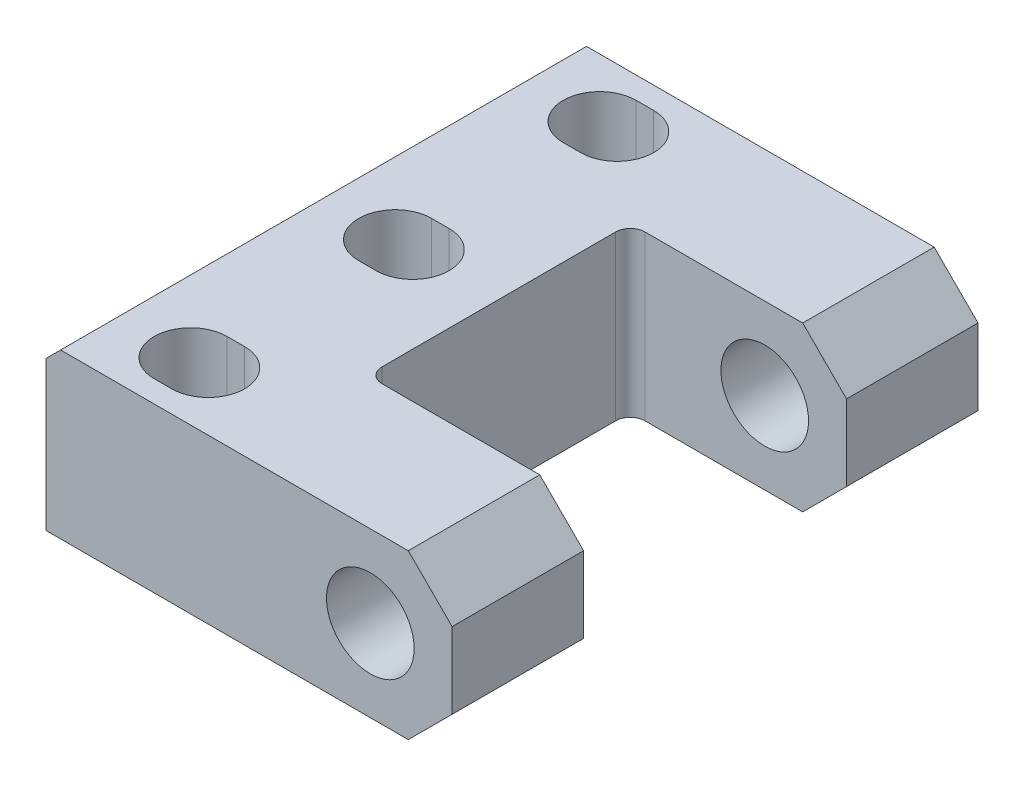
SolidWorks part; units mm, degrees
ref_plane "前视基准面" through (0, 0, 0) normal (0, 0, 1) x (1, 0, 0)
ref_plane "上视基准面" through (0, 0, 0) normal (0, 1, 0) x (1, 0, 0)
ref_plane "右视基准面" through (0, 0, 0) normal (1, 0, 0) x (0, 0, -1)
sketch "草图1" plane through (0, 0, 0) normal (0, 1, 0) x (1, 0, 0)
  line L0 (0, -90) -> (0, 90)
  line L1 (0, 90) -> (139, 90)
  line L2 (139, 90) -> (139, 45)
  line L3 (139, 45) -> (65, 45)
  line L4 (65, 45) -> (65, -45)
  line L5 (0, 0) -> (-68.1514, 0) construction
  line L6 (139, -45) -> (65, -45)
  line L7 (139, -90) -> (139, -45)
  line L8 (0, -90) -> (139, -90)
  point P9 (65, 0)
  dimension "D1" = 180
  dimension "D2" = 90
  dimension "D3" = 139
  dimension "D4" = 74
extrude "凸台-拉伸1" add sketch "草图1" against normal blind 56
sketch "草图2" plane through (0, 0, 0) normal (0, 1, 0) x (1, 0, 0)
  line L0 (0, 0) -> (-30.2002, 0) construction
  line L1 (0, 90) -> (0, -90) construction
  line L2 (29.5, 70) -> (35.5, 70) construction
  line L3 (29.5, 78.5) -> (35.5, 78.5)
  line L4 (29.5, 61.5) -> (35.5, 61.5)
  arc A0 (29.5, 78.5) -> (29.5, 61.5) centre (29.5, 70) ccw
  arc A1 (35.5, 61.5) -> (35.5, 78.5) centre (35.5, 70) ccw
  point P6 (32.5, 70)
  dimension "D1" = 17
  dimension "D2" = 6
  dimension "D3" = 32.5
  dimension "D4" = 70
extrude "切除-拉伸1" cut sketch "草图2" against normal up to next
sketch "草图3" plane through (0, 0, 0) normal (0, 1, 0) x (1, 0, 0)
  line L8 (139, 90) -> (0, 90)
  line L9 (0, 90) -> (0, -90)
  line L10 (0, -90) -> (139, -90)
  line L11 (139, -90) -> (139, -45)
  line L12 (139, -45) -> (65, -45)
  line L13 (65, -45) -> (65, 45)
  line L14 (65, 45) -> (139, 45)
  line L15 (139, 45) -> (139, 90)
  line L16 (139, 90) -> (0, 90)
  line L17 (0, 90) -> (0, -90)
  line L18 (0, -90) -> (139, -90)
  line L19 (139, -90) -> (139, -45)
  line L20 (139, -45) -> (65, -45)
  line L21 (65, -45) -> (65, 45)
  line L22 (65, 45) -> (139, 45)
  line L23 (139, 45) -> (139, 90)
  line L27 (29.5, 57.5) -> (35.5, 57.5)
  line L28 (35.5, 82.5) -> (29.5, 82.5)
  line L29 (29.5, 57.5) -> (35.5, 57.5)
  line L30 (35.5, 82.5) -> (29.5, 82.5)
  arc A2 (35.5, 61.5) -> (35.5, 78.5) centre (35.5, 70) ccw construction
  arc A15 (35.5, 57.5) -> (35.5, 82.5) centre (35.5, 70) ccw
  arc A16 (29.5, 82.5) -> (29.5, 57.5) centre (29.5, 70) ccw
  arc A17 (35.5, 57.5) -> (35.5, 82.5) centre (35.5, 70) ccw
  arc A18 (29.5, 82.5) -> (29.5, 57.5) centre (29.5, 70) ccw
  point P29 (44, 70)
  dimension "D1" = 0
  dimension "D2" = 4
extrude "切除-拉伸2" cut sketch "草图3" against normal blind 24 contours A18 L29 A17 L30
pattern_linear "阵列(线性)1" count 3 spacing 70 along (0, 0, 1) of "切除-拉伸2", "切除-拉伸1"
sketch "草图4" plane through (0, 0, 90) normal (0, 0, 1) x (1, 0, 0)
  line L0 (0, -28) -> (156.4852, -28) construction
  line L1 (0, -56) -> (0, 0) construction
  circle A1 centre (111, -28) radius 15
  dimension "D1" = 30
  dimension "D2" = 111
extrude "切除-拉伸3" cut sketch "草图4" against normal through all
chamfer "倒角1" distance 5 1 edges at (0, 0, 0)
chamfer "倒角2" distance 15 angle 45 4 edges at (139, -56, -67.5) (139, -56, 67.5) (139, 0, 67.5) (139, 0, -67.5)
fillet "圆角1" radius 5 2 edges at (65, -28, -45) (65, -28, 45)
